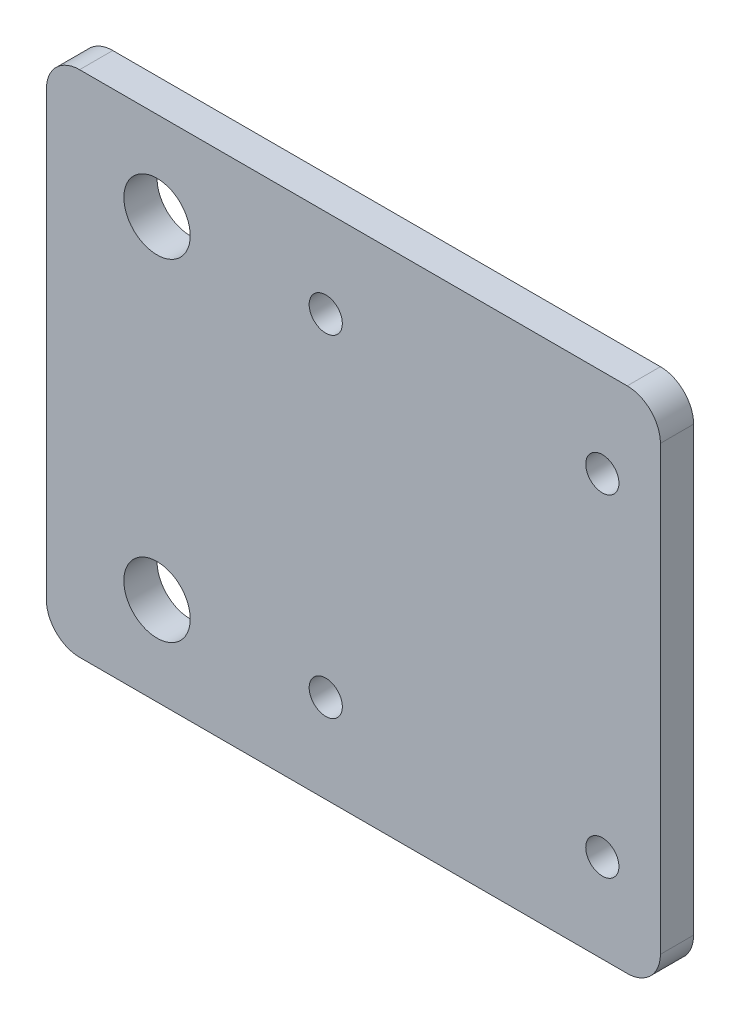
SolidWorks part; units mm, degrees
ref_plane "前视基准面" through (0, 0, 0) normal (0, 0, 1) x (1, 0, 0)
ref_plane "上视基准面" through (0, 0, 0) normal (0, 1, 0) x (1, 0, 0)
ref_plane "右视基准面" through (0, 0, 0) normal (1, 0, 0) x (0, 0, -1)
sketch "草图1" plane through (0, 0, 0) normal (0, 0, 1) x (1, 0, 0)
  line L0 (56.9644, -13.7486) -> (56.9644, 26.2514)
  line L1 (53.9644, 29.2514) -> (4.4644, 29.2514)
  line L2 (1.4644, 26.2514) -> (1.4644, -13.7486)
  line L3 (4.4644, -16.7486) -> (53.9644, -16.7486)
  line L4 (-15.2152, 6.2514) -> (69.8514, 6.2514) construction
  line L5 (11.4644, 46.5662) -> (11.4644, -24.5714) construction
  circle A0 centre (51.7144, 21.2514) radius 1.5
  arc A3 (1.4644, -13.7486) -> (4.4644, -16.7486) centre (4.4644, -13.7486) ccw
  circle A5 centre (26.7144, 21.2514) radius 1.5
  arc A8 (56.9644, 26.2514) -> (53.9644, 29.2514) centre (53.9644, 26.2514) ccw
  circle A9 centre (26.7144, -8.7486) radius 1.5
  circle A10 centre (51.7144, -8.7486) radius 1.5
  arc A11 (1.4644, 26.2514) -> (4.4644, 29.2514) centre (4.4644, 26.2514) cw
  arc A12 (53.9644, -16.7486) -> (56.9644, -13.7486) centre (53.9644, -13.7486) ccw
  circle A13 centre (11.4644, 21.2514) radius 3
  circle A14 centre (11.4644, -8.7486) radius 3
  point P22 (1.4644, 6.2514)
  point P23 (56.9644, 6.2514)
  dimension "D1" = 3
  dimension "D4" = 3
  dimension "D2" = 3
  dimension "D6" = 3
  dimension "D9" = 6
  dimension "D3" = 30
  dimension "D5" = 25
  dimension "D7" = 55.5
  dimension "D8" = 10
  dimension "D10" = 30
extrude "凸台-拉伸1" add sketch "草图1" along normal blind 3
